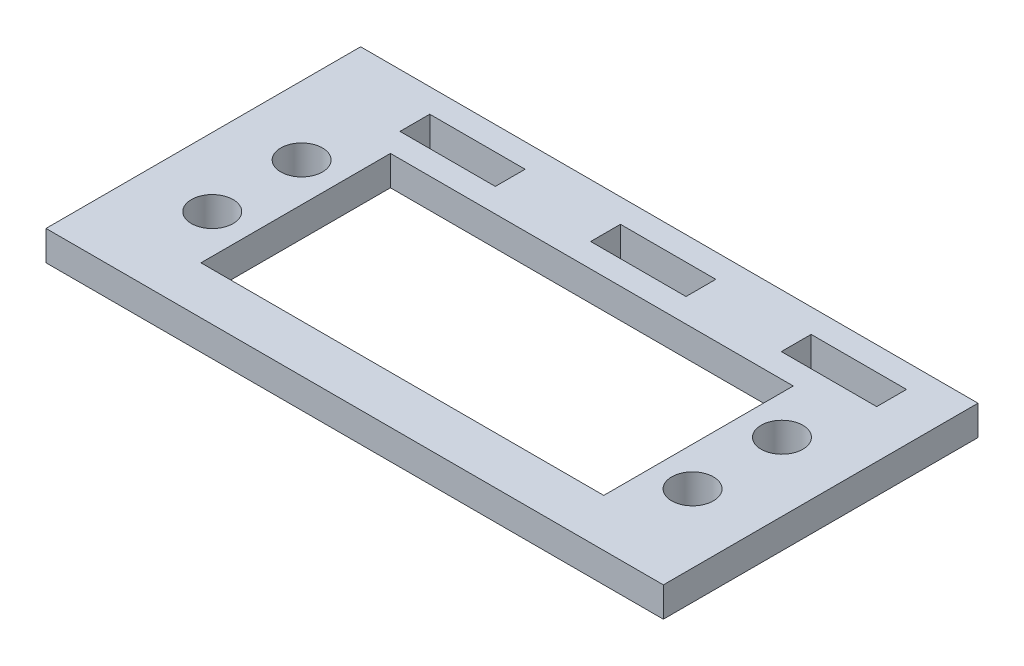
SolidWorks part; units mm, degrees
ref_plane "Front Plane" through (0, 0, 0) normal (0, 0, 1) x (1, 0, 0)
ref_plane "Top Plane" through (0, 0, 0) normal (0, 1, 0) x (1, 0, 0)
ref_plane "Right Plane" through (0, 0, 0) normal (1, 0, 0) x (0, 0, -1)
sketch "Sketch1" plane through (0, 0, 0) normal (0, 1, 0) x (1, 0, 0)
  line L0 (27.813, -10.0965) -> (32.893, -10.0965) construction
  line L1 (32.893, 18.3515) -> (-32.893, 18.3515)
  line L2 (32.893, 18.3515) -> (32.893, -15.1765)
  line L3 (32.893, -15.1765) -> (-32.893, -15.1765)
  line L4 (-32.893, 18.3515) -> (-32.893, -15.1765)
  line L5 (27.813, -10.0965) -> (27.813, -15.1765) construction
  line L6 (-27.813, -10.0965) -> (-32.893, -10.0965) construction
  line L7 (-27.813, 10.0965) -> (27.813, 10.0965) construction
  line L8 (-27.813, 10.0965) -> (-27.813, -10.0965) construction
  line L9 (-27.813, -10.0965) -> (27.813, -10.0965) construction
  line L10 (27.813, 10.0965) -> (27.813, -10.0965) construction
  line L11 (-27.813, 10.0965) -> (27.813, -10.0965) construction
  line L12 (-27.813, -10.0965) -> (27.813, 10.0965) construction
  line L13 (27.813, 15.8115) -> (27.813, 18.3515) construction
  line L14 (27.813, 15.8115) -> (17.653, 15.8115)
  line L15 (27.813, 15.8115) -> (27.813, 12.6365)
  line L16 (27.813, 12.6365) -> (17.653, 12.6365)
  line L17 (17.653, 15.8115) -> (17.653, 12.6365)
  line L18 (27.813, 15.8115) -> (17.653, 12.6365) construction
  line L19 (27.813, 12.6365) -> (17.653, 15.8115) construction
  line L20 (27.813, 12.6365) -> (27.813, 10.0965) construction
  line L21 (7.493, 15.8115) -> (7.493, 12.6365)
  line L22 (7.493, 15.8115) -> (-2.667, 15.8115)
  line L23 (7.493, 12.6365) -> (-2.667, 12.6365)
  line L24 (-2.667, 15.8115) -> (-2.667, 12.6365)
  line L25 (-12.827, 15.8115) -> (-12.827, 12.6365)
  line L26 (-12.827, 15.8115) -> (-22.987, 15.8115)
  line L27 (-12.827, 12.6365) -> (-22.987, 12.6365)
  line L28 (-22.987, 15.8115) -> (-22.987, 12.6365)
  line L29 (-21.463, 0) -> (-27.813, 0) construction
  line L30 (-21.463, -10.0965) -> (21.463, -10.0965)
  line L31 (-21.463, -10.0965) -> (-21.463, 10.0965)
  line L32 (-21.463, 10.0965) -> (21.463, 10.0965)
  line L33 (21.463, -10.0965) -> (21.463, 10.0965)
  line L34 (-21.463, -10.0965) -> (21.463, 10.0965) construction
  line L35 (-21.463, 10.0965) -> (21.463, -10.0965) construction
  line L36 (21.463, 0) -> (27.813, 0) construction
  line L37 (-27.813, 9.525) -> (27.813, 9.525) construction
  line L38 (-27.813, -9.525) -> (27.813, -9.525) construction
  line L39 (-25.5905, 9.525) -> (-25.5905, 0) construction
  line L40 (-25.5905, 0) -> (-25.5905, -9.525) construction
  line L41 (-25.5905, 4.7625) -> (25.5905, 4.7625) construction
  line L42 (-25.5905, -4.7625) -> (25.5905, -4.7625) construction
  circle A0 centre (-25.5905, 4.7625) radius 2.2225
  circle A1 centre (-25.5905, -4.7625) radius 2.2225
  circle A2 centre (25.5905, 4.7625) radius 2.2225
  circle A3 centre (25.5905, -4.7625) radius 2.2225
  point P0 (0, 0)
  point P4 (22.733, 14.224)
  point P6 (0, 0)
  point P20 (0, 0)
  dimension "D9" = 4.445
  dimension "D1" = 20.193
  dimension "D2" = 55.626
  dimension "D3" = 5.08
  dimension "D4" = 3.175
  dimension "D5" = 10.16
  dimension "D6" = 2.54
  dimension "D7" = 3
  dimension "D8" = 6.35
  dimension "D10" = 19.05
extrude "Boss-Extrude2" add sketch "Sketch1" along normal blind 3.175
sketch "Sketch3" plane through (0, 3.175, 0) normal (0, 1, 0) x (1, 0, 0)
  line L8 (27.7368, 12.7127) -> (27.7368, 15.7353)
  line L9 (17.7292, 15.7353) -> (17.7292, 12.7127)
  line L10 (27.7368, 15.7353) -> (17.7292, 15.7353)
  line L11 (17.7292, 12.7127) -> (27.7368, 12.7127)
  line L12 (27.7368, 12.7127) -> (27.7368, 15.7353)
  line L13 (17.7292, 15.7353) -> (17.7292, 12.7127)
  line L14 (27.7368, 15.7353) -> (17.7292, 15.7353)
  line L15 (17.7292, 12.7127) -> (27.7368, 12.7127)
  line L20 (7.4168, 12.7127) -> (7.4168, 15.7353)
  line L21 (7.4168, 15.7353) -> (-2.5908, 15.7353)
  line L22 (-2.5908, 15.7353) -> (-2.5908, 12.7127)
  line L23 (-2.5908, 12.7127) -> (7.4168, 12.7127)
  line L24 (7.4168, 12.7127) -> (7.4168, 15.7353)
  line L25 (7.4168, 15.7353) -> (-2.5908, 15.7353)
  line L26 (-2.5908, 15.7353) -> (-2.5908, 12.7127)
  line L27 (-2.5908, 12.7127) -> (7.4168, 12.7127)
  line L32 (-22.9108, 15.7353) -> (-22.9108, 12.7127)
  line L33 (-12.9032, 15.7353) -> (-22.9108, 15.7353)
  line L34 (-12.9032, 12.7127) -> (-12.9032, 15.7353)
  line L35 (-22.9108, 12.7127) -> (-12.9032, 12.7127)
  line L36 (-22.9108, 15.7353) -> (-22.9108, 12.7127)
  line L37 (-12.9032, 15.7353) -> (-22.9108, 15.7353)
  line L38 (-12.9032, 12.7127) -> (-12.9032, 15.7353)
  line L39 (-22.9108, 12.7127) -> (-12.9032, 12.7127)
  line L44 (32.9692, -15.2527) -> (32.9692, 18.4277)
  line L45 (-32.9692, -15.2527) -> (32.9692, -15.2527)
  line L46 (-32.9692, 18.4277) -> (-32.9692, -15.2527)
  line L47 (32.9692, 18.4277) -> (-32.9692, 18.4277)
  line L48 (32.9692, -15.2527) -> (32.9692, 18.4277)
  line L49 (-32.9692, -15.2527) -> (32.9692, -15.2527)
  line L50 (-32.9692, 18.4277) -> (-32.9692, -15.2527)
  line L51 (32.9692, 18.4277) -> (-32.9692, 18.4277)
  line L56 (-21.463, -10.0965) -> (21.463, -10.0965)
  line L57 (21.463, -10.0965) -> (21.463, 10.0965)
  line L58 (21.463, 10.0965) -> (-21.463, 10.0965)
  line L59 (-21.463, 10.0965) -> (-21.463, -10.0965)
  line L60 (-21.463, -10.0965) -> (21.463, -10.0965)
  line L61 (21.463, -10.0965) -> (21.463, 10.0965)
  line L62 (21.463, 10.0965) -> (-21.463, 10.0965)
  line L63 (-21.463, 10.0965) -> (-21.463, -10.0965)
  circle A2 centre (-25.5905, 4.7625) radius 2.1463
  circle A3 centre (-25.5905, 4.7625) radius 2.1463
  circle A5 centre (-25.5905, -4.7625) radius 2.1463
  circle A6 centre (-25.5905, -4.7625) radius 2.1463
  circle A8 centre (25.5905, 4.7625) radius 2.1463
  circle A9 centre (25.5905, 4.7625) radius 2.1463
  circle A11 centre (25.5905, -4.7625) radius 2.1463
  circle A12 centre (25.5905, -4.7625) radius 2.1463
  dimension "D1" = 0.0762
  dimension "D2" = 0.0762
  dimension "D3" = 0.0762
  dimension "D4" = 0.0762
  dimension "D5" = 0.0762
  dimension "D6" = 0.0762
  dimension "D7" = 0.0762
  dimension "D8" = 0.0762
  dimension "D9" = 0
